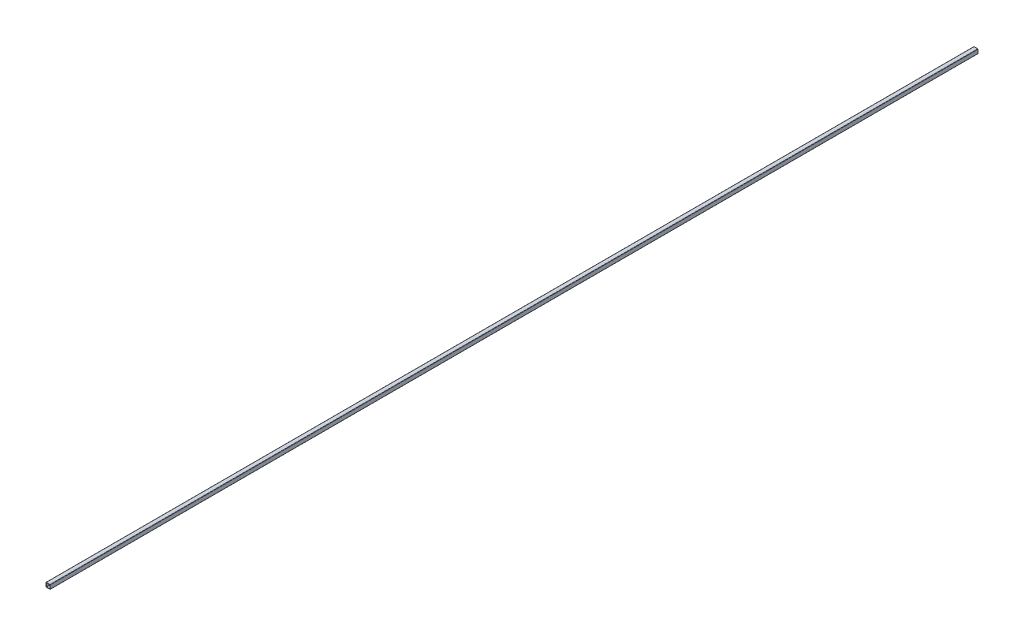
SolidWorks part; units mm, degrees
material "ASTM A500 Grade B Steel"
ref_plane "Front Plane" through (0, 0, 0) normal (0, 0, 1) x (1, 0, 0)
ref_plane "Top Plane" through (0, 0, 0) normal (0, 1, 0) x (1, 0, 0)
ref_plane "Right Plane" through (0, 0, 0) normal (1, 0, 0) x (0, 0, -1)
sketch "Sketch1" plane through (0, 0, 0) normal (0, 0, 1) x (1, 0, 0)
  line L0 (5.3086, -2.7686) -> (32.7914, -2.7686)
  line L1 (2.54, 0) -> (35.56, 0)
  line L2 (0, -2.54) -> (0, -35.56)
  line L3 (2.54, -38.1) -> (35.56, -38.1)
  line L4 (38.1, -2.54) -> (38.1, -35.56)
  line L5 (35.3314, -5.3086) -> (35.3314, -32.7914)
  line L6 (5.3086, -35.3314) -> (32.7914, -35.3314)
  line L7 (2.7686, -5.3086) -> (2.7686, -32.7914)
  line L8 (0, 0) -> (0, -38.1) construction
  line L9 (0, -38.1) -> (38.1, -38.1) construction
  line L10 (38.1, 0) -> (38.1, -38.1) construction
  line L11 (2.7686, -2.7686) -> (2.7686, -35.3314) construction
  line L12 (2.7686, -35.3314) -> (35.3314, -35.3314) construction
  line L13 (35.3314, -2.7686) -> (35.3314, -35.3314) construction
  line L14 (2.7686, -2.7686) -> (35.3314, -2.7686) construction
  line L15 (0, 0) -> (38.1, 0) construction
  arc A0 (0, -35.56) -> (2.54, -38.1) centre (2.54, -35.56) ccw
  arc A1 (38.1, -35.56) -> (35.56, -38.1) centre (35.56, -35.56) cw
  arc A2 (2.7686, -32.7914) -> (5.3086, -35.3314) centre (5.3086, -32.7914) ccw
  arc A3 (32.7914, -35.3314) -> (35.3314, -32.7914) centre (32.7914, -32.7914) ccw
  arc A4 (35.3314, -5.3086) -> (32.7914, -2.7686) centre (32.7914, -5.3086) ccw
  arc A5 (38.1, -2.54) -> (35.56, 0) centre (35.56, -2.54) ccw
  arc A6 (0, -2.54) -> (2.54, 0) centre (2.54, -2.54) cw
  arc A7 (5.3086, -2.7686) -> (2.7686, -5.3086) centre (5.3086, -5.3086) ccw
  point P12 (0, -38.1)
  dimension "D4" = 2.54
  dimension "D3" = 2.7686
extrude "Boss-Extrude1" add sketch "Sketch1" along normal blind 8380
fillet "Fillet1" radius 1 32 edges at (2.7686, -19.05, 0) (3.5125, -3.5125, 0) (19.05, -2.7686, 0) (34.5875, -3.5125, 0) (35.3314, -19.05, 0) (34.5875, -34.5875, 0) (19.05, -35.3314, 0) (3.5125, -34.5875, 0) (19.05, -38.1, 0) (37.3561, -37.3561, 0) (38.1, -19.05, 0) (37.3561, -0.7439, 0) (19.05, 0, 0) (0.7439, -0.7439, 0) (0, -19.05, 0) (0.7439, -37.3561, 0) (34.5875, -34.5875, 8380) (35.3314, -19.05, 8380) (34.5875, -3.5125, 8380) (19.05, -2.7686, 8380) (3.5125, -3.5125, 8380) (2.7686, -19.05, 8380) (3.5125, -34.5875, 8380) (19.05, -35.3314, 8380) (0, -19.05, 8380) (0.7439, -0.7439, 8380) (19.05, 0, 8380) (37.3561, -0.7439, 8380) (38.1, -19.05, 8380) (37.3561, -37.3561, 8380) (19.05, -38.1, 8380) (0.7439, -37.3561, 8380)
